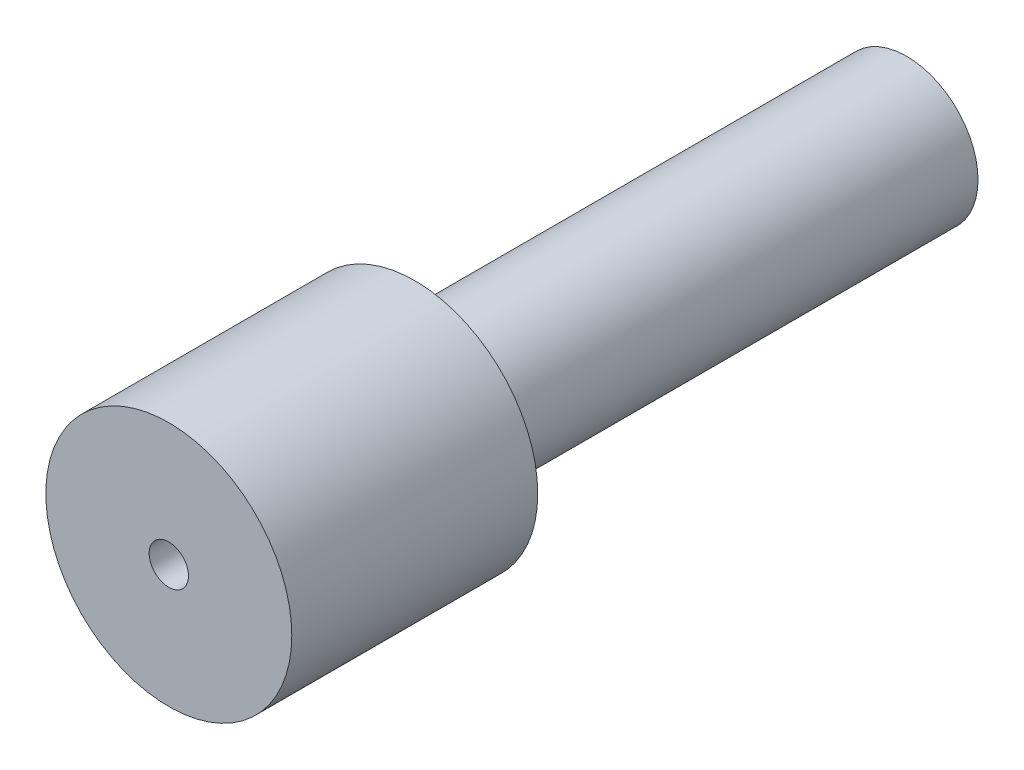
SolidWorks part; units mm, degrees
ref_plane "Front Plane" through (0, 0, 0) normal (0, 0, 1) x (1, 0, 0)
ref_plane "Top Plane" through (0, 0, 0) normal (0, 1, 0) x (1, 0, 0)
ref_plane "Right Plane" through (0, 0, 0) normal (1, 0, 0) x (0, 0, -1)
sketch "Sketch2" plane through (0, 0, 0) normal (0, 1, 0) x (1, 0, 0)
  line L0 (0, 0) -> (0, 87.5643) construction
  line L1 (-1.016, 0) -> (-6.35, 0)
  line L2 (-6.35, 0) -> (-6.35, 12.7)
  line L3 (-6.35, 12.7) -> (-4.953, 12.7)
  line L4 (-4.953, 12.7) -> (-3.683, 13.97)
  line L5 (-3.683, 13.97) -> (-3.683, 38.1)
  line L6 (-3.683, 38.1) -> (-2.0955, 38.1)
  line L7 (-2.0955, 38.1) -> (-2.0955, 10.16)
  line L8 (-2.0955, 10.16) -> (-1.016, 10.16)
  line L9 (-1.016, 10.16) -> (-1.016, 0)
  dimension "D1" = 12.7
  dimension "D2" = 25.4
  dimension "D3" = 1.016
  dimension "D4" = 6.35
  dimension "D5" = 1.27
  dimension "D6" = 1.27
  dimension "D7" = 2.0955
  dimension "D8" = 3.683
  dimension "D9" = 10.16
revolve "Revolve1" add sketch "Sketch2" angle 360 about L0
